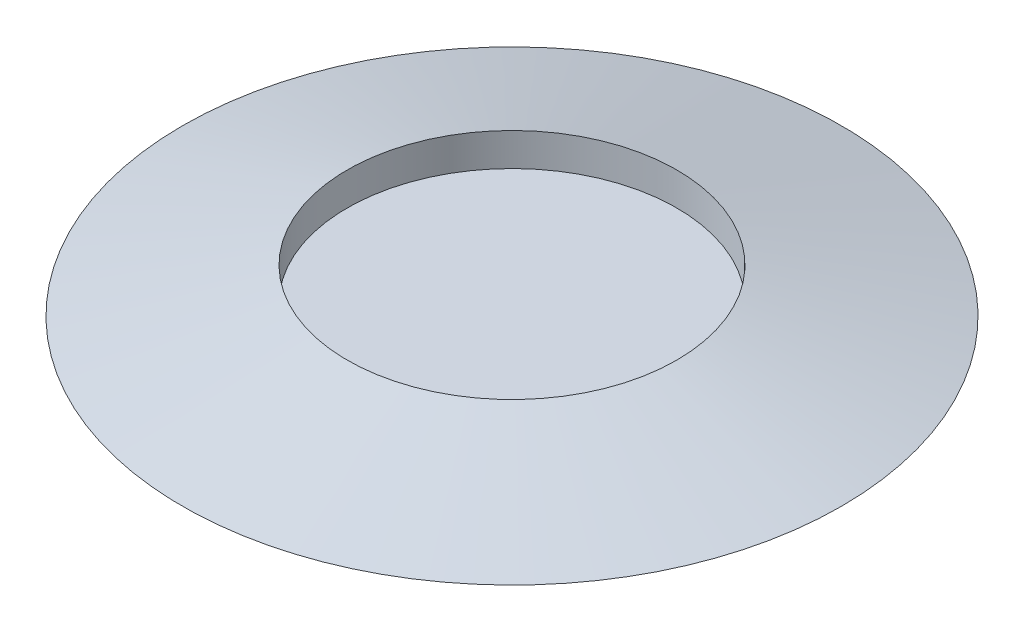
SolidWorks part; units mm, degrees
ref_plane "Front Plane" through (0, 0, 0) normal (0, 0, 1) x (1, 0, 0)
ref_plane "Top Plane" through (0, 0, 0) normal (0, 1, 0) x (1, 0, 0)
ref_plane "Right Plane" through (0, 0, 0) normal (1, 0, 0) x (0, 0, -1)
sketch "Sketch1" plane through (0, 0, 0) normal (0, 0, 1) x (1, 0, 0)
  line L0 (0, 0) -> (0, 53.5898)
  line L1 (0, 53.5898) -> (-200, 0)
  line L2 (-200, 0) -> (0, 0)
  line L3 (-100, 26.7949) -> (-100, 6.7949)
  line L4 (-100, 6.7949) -> (0, 6.7949)
  dimension "D1" = 200
  dimension "D2" = 15
  dimension "D3" = 100
  dimension "D4" = 20
revolve "Revolve1" add sketch "Sketch1" angle 360 about L0
